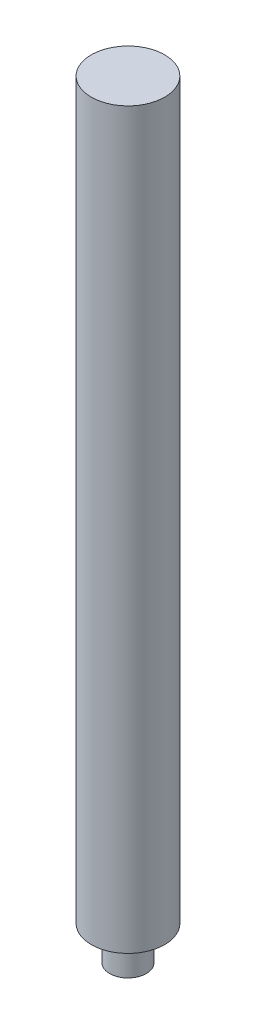
SolidWorks part; units mm, degrees
ref_plane "前基準面" through (0, 0, 0) normal (0, 0, 1) x (1, 0, 0)
ref_plane "上基準面" through (0, 0, 0) normal (0, 1, 0) x (1, 0, 0)
ref_plane "右基準面" through (0, 0, 0) normal (1, 0, 0) x (0, 0, -1)
sketch "草圖1" plane through (0, 0, 0) normal (0, 1, 0) x (1, 0, 0)
  circle A0 centre (0, 0) radius 1.5
extrude "填料-伸長1" add sketch "草圖1" along normal blind 2.8
sketch "草圖2" plane through (0, 2.8, 0) normal (0, 1, 0) x (1, 0, 0)
  circle A0 centre (0, 0) radius 3
extrude "填料-伸長2" add sketch "草圖2" along normal blind 60
